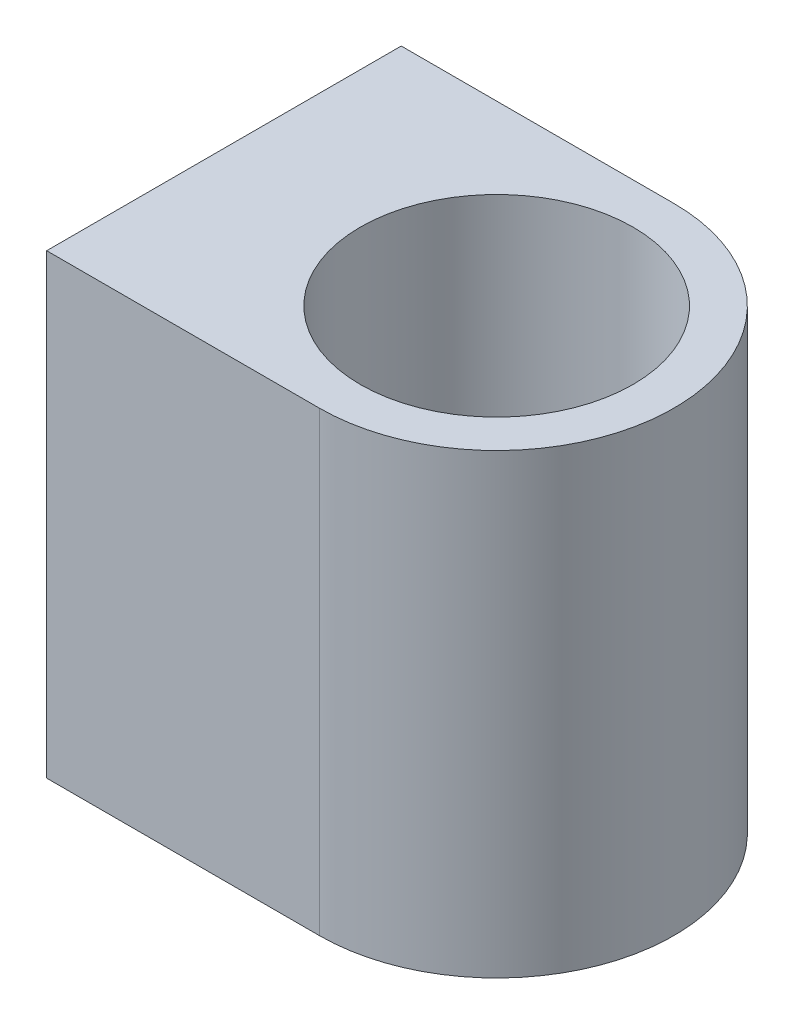
SolidWorks part; units mm, degrees
ref_plane "Front Plane" through (0, 0, 0) normal (0, 0, 1) x (1, 0, 0)
ref_plane "Top Plane" through (0, 0, 0) normal (0, 1, 0) x (1, 0, 0)
ref_plane "Right Plane" through (0, 0, 0) normal (1, 0, 0) x (0, 0, -1)
sketch "Sketch1" plane through (0, 0, 0) normal (0, 1, 0) x (1, 0, 0)
  line L0 (0, 0) -> (0, 13)
  line L1 (0, 0) -> (0, -13)
  line L2 (0, 13) -> (20, 13)
  line L3 (0, -13) -> (20, -13)
  arc A0 (20, -13) -> (20, 13) centre (20, 0) ccw
extrude "Boss-Extrude2" add sketch "Sketch1" against normal blind 33.5
sketch "Sketch2" plane through (0, 0, 0) normal (0, 1, 0) x (1, 0, 0)
  circle A0 centre (20, 0) radius 10
extrude "Cut-Extrude1" cut sketch "Sketch2" against normal through all
